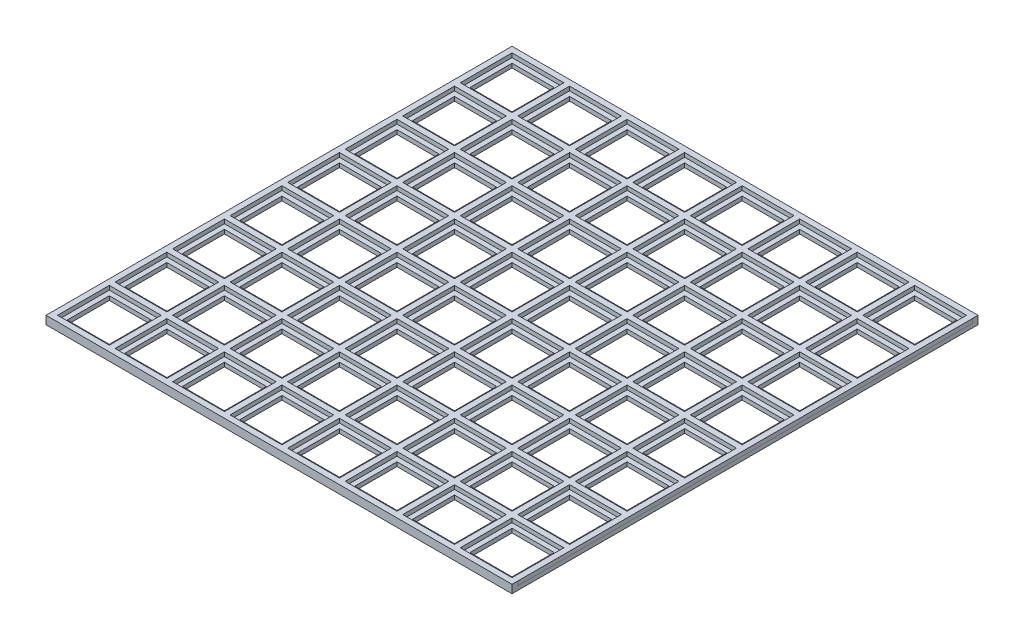
SolidWorks part; units mm, degrees
ref_plane "Front Plane" through (0, 0, 0) normal (0, 0, 1) x (1, 0, 0)
ref_plane "Top Plane" through (0, 0, 0) normal (0, 1, 0) x (1, 0, 0)
ref_plane "Right Plane" through (0, 0, 0) normal (1, 0, 0) x (0, 0, -1)
sketch "Sketch5" plane through (0, 0, 0) normal (1, 0, 0) x (0, 0, -1)
  line L4 (-23.4192, -2.2554) -> (-23.4192, 2.8246)
  line L5 (-23.4192, 2.8246) -> (-19.8632, 2.8246)
  line L6 (-19.8632, 2.8246) -> (-19.8632, 0.2846)
  line L7 (-19.8632, 0.2846) -> (261.0568, 0.2846)
  line L11 (261.0568, 0.2846) -> (261.0568, 2.8246)
  line L12 (261.0568, 2.8246) -> (264.6128, 2.8246)
  line L13 (264.6128, 2.8246) -> (264.6128, -2.2554)
  line L20 (-19.8632, -2.2554) -> (261.0528, -2.2554)
  line L26 (-19.8632, -2.2554) -> (-23.4192, -2.2554)
  line L27 (261.0528, -2.2554) -> (264.6128, -2.2554)
  dimension "D3" = 3.556
  dimension "D4" = 3.556
  dimension "D9" = 2.54
  dimension "D12" = 2.54
  dimension "D14" = 280.92
  dimension "D16" = 2.54
extrude "Boss-Extrude3" add sketch "Sketch5" along normal blind 288.04
sketch "Sketch7" plane through (0, 0.2846, 0) normal (0, 1, 0) x (1, 0, 0)
  line L0 (288.04, 261.0568) -> (0, 261.0568) construction
  line L1 (0.0237, 261.0568) -> (3.5797, 261.0568)
  line L2 (0.0237, 261.0568) -> (0.0237, -19.8632)
  line L3 (0.0237, -19.8632) -> (3.5797, -19.8632)
  line L4 (3.5797, 261.0568) -> (3.5797, -19.8632)
  line L5 (288.04, -19.8632) -> (0, -19.8632) construction
  line L6 (35.5837, 261.0568) -> (35.5837, -19.8632)
  line L7 (35.5837, 261.0568) -> (39.1397, 261.0568)
  line L8 (39.1397, 261.0568) -> (39.1397, -19.8632)
  line L9 (35.5837, -19.8632) -> (39.1397, -19.8632)
  line L10 (71.1437, 261.0568) -> (71.1437, -19.8632)
  line L11 (71.1437, 261.0568) -> (74.6997, 261.0568)
  line L12 (74.6997, 261.0568) -> (74.6997, -19.8632)
  line L13 (71.1437, -19.8632) -> (74.6997, -19.8632)
  line L14 (106.7037, 261.0568) -> (106.7037, -19.8632)
  line L15 (106.7037, 261.0568) -> (110.2597, 261.0568)
  line L16 (110.2597, 261.0568) -> (110.2597, -19.8632)
  line L17 (106.7037, -19.8632) -> (110.2597, -19.8632)
  line L18 (142.2637, 261.0568) -> (142.2637, -19.8632)
  line L19 (142.2637, 261.0568) -> (145.8197, 261.0568)
  line L20 (145.8197, 261.0568) -> (145.8197, -19.8632)
  line L21 (142.2637, -19.8632) -> (145.8197, -19.8632)
  line L22 (177.8237, 261.0568) -> (177.8237, -19.8632)
  line L23 (177.8237, 261.0568) -> (181.3797, 261.0568)
  line L24 (181.3797, 261.0568) -> (181.3797, -19.8632)
  line L25 (177.8237, -19.8632) -> (181.3797, -19.8632)
  line L26 (213.3837, 261.0568) -> (213.3837, -19.8632)
  line L27 (213.3837, 261.0568) -> (216.9397, 261.0568)
  line L28 (216.9397, 261.0568) -> (216.9397, -19.8632)
  line L29 (213.3837, -19.8632) -> (216.9397, -19.8632)
  line L30 (248.9437, 261.0568) -> (248.9437, -19.8632)
  line L31 (248.9437, 261.0568) -> (252.4997, 261.0568)
  line L32 (252.4997, 261.0568) -> (252.4997, -19.8632)
  line L33 (248.9437, -19.8632) -> (252.4997, -19.8632)
  line L34 (284.5037, 261.0568) -> (284.5037, -19.8632)
  line L35 (284.5037, 261.0568) -> (288.0597, 261.0568)
  line L36 (288.0597, 261.0568) -> (288.0597, -19.8632)
  line L37 (284.5037, -19.8632) -> (288.0597, -19.8632)
  line L38 (0.0337, -19.8632) -> (0.0337, -23.4192)
  line L39 (0.0237, -19.8632) -> (288.04, -19.8632)
  line L40 (0.0237, -19.8632) -> (0.0237, -23.4192)
  line L41 (0.0237, -23.4192) -> (288.04, -23.4192)
  line L42 (288.04, -19.8632) -> (288.04, -23.4192)
  line L43 (0.0337, -19.8632) -> (288.05, -19.8632)
  line L44 (288.05, -19.8632) -> (288.05, -23.4192)
  line L45 (0.0337, -23.4192) -> (288.05, -23.4192)
  line L46 (0.0337, 15.6968) -> (0.0337, 12.1408)
  line L47 (0.0337, 15.6968) -> (288.05, 15.6968)
  line L48 (288.05, 15.6968) -> (288.05, 12.1408)
  line L49 (0.0337, 12.1408) -> (288.05, 12.1408)
  line L50 (0.0337, 51.2568) -> (0.0337, 47.7008)
  line L51 (0.0337, 51.2568) -> (288.05, 51.2568)
  line L52 (288.05, 51.2568) -> (288.05, 47.7008)
  line L53 (0.0337, 47.7008) -> (288.05, 47.7008)
  line L54 (0.0337, 86.8168) -> (0.0337, 83.2608)
  line L55 (0.0337, 86.8168) -> (288.05, 86.8168)
  line L56 (288.05, 86.8168) -> (288.05, 83.2608)
  line L57 (0.0337, 83.2608) -> (288.05, 83.2608)
  line L58 (0.0337, 122.3768) -> (0.0337, 118.8208)
  line L59 (0.0337, 122.3768) -> (288.05, 122.3768)
  line L60 (288.05, 122.3768) -> (288.05, 118.8208)
  line L61 (0.0337, 118.8208) -> (288.05, 118.8208)
  line L62 (0.0337, 157.9368) -> (0.0337, 154.3808)
  line L63 (0.0337, 157.9368) -> (288.05, 157.9368)
  line L64 (288.05, 157.9368) -> (288.05, 154.3808)
  line L65 (0.0337, 154.3808) -> (288.05, 154.3808)
  line L66 (0.0337, 193.4968) -> (0.0337, 189.9408)
  line L67 (0.0337, 193.4968) -> (288.05, 193.4968)
  line L68 (288.05, 193.4968) -> (288.05, 189.9408)
  line L69 (0.0337, 189.9408) -> (288.05, 189.9408)
  line L70 (0.0337, 229.0568) -> (0.0337, 225.5008)
  line L71 (0.0337, 229.0568) -> (288.05, 229.0568)
  line L72 (288.05, 229.0568) -> (288.05, 225.5008)
  line L73 (0.0337, 225.5008) -> (288.05, 225.5008)
  line L74 (0.0337, 264.6168) -> (0.0337, 261.0608)
  line L75 (0.0337, 264.6168) -> (288.05, 264.6168)
  line L76 (288.05, 264.6168) -> (288.05, 261.0608)
  line L77 (0.0337, 261.0608) -> (288.05, 261.0608)
  line L78 (0.0237, 15.6968) -> (0.0237, 12.1408)
  line L79 (0.0237, 15.6968) -> (288.04, 15.6968)
  line L80 (288.04, 15.6968) -> (288.04, 12.1408)
  line L81 (0.0237, 12.1408) -> (288.04, 12.1408)
  line L82 (0.0237, 51.2568) -> (0.0237, 47.7008)
  line L83 (0.0237, 51.2568) -> (288.04, 51.2568)
  line L84 (288.04, 51.2568) -> (288.04, 47.7008)
  line L85 (0.0237, 47.7008) -> (288.04, 47.7008)
  line L86 (0.0237, 86.8168) -> (0.0237, 83.2608)
  line L87 (0.0237, 86.8168) -> (288.04, 86.8168)
  line L88 (288.04, 86.8168) -> (288.04, 83.2608)
  line L89 (0.0237, 83.2608) -> (288.04, 83.2608)
  line L90 (0.0237, 122.3768) -> (0.0237, 118.8208)
  line L91 (0.0237, 122.3768) -> (288.04, 122.3768)
  line L92 (288.04, 122.3768) -> (288.04, 118.8208)
  line L93 (0.0237, 118.8208) -> (288.04, 118.8208)
  line L94 (0.0237, 157.9368) -> (0.0237, 154.3808)
  line L95 (0.0237, 157.9368) -> (288.04, 157.9368)
  line L96 (288.04, 157.9368) -> (288.04, 154.3808)
  line L97 (0.0237, 154.3808) -> (288.04, 154.3808)
  line L98 (0.0237, 193.4968) -> (0.0237, 189.9408)
  line L99 (0.0237, 193.4968) -> (288.04, 193.4968)
  line L100 (288.04, 193.4968) -> (288.04, 189.9408)
  line L101 (0.0237, 189.9408) -> (288.04, 189.9408)
  line L102 (0.0237, 229.0568) -> (0.0237, 225.5008)
  line L103 (0.0237, 229.0568) -> (288.04, 229.0568)
  line L104 (288.04, 229.0568) -> (288.04, 225.5008)
  line L105 (0.0237, 225.5008) -> (288.04, 225.5008)
  line L106 (0.0237, 264.6168) -> (0.0237, 261.0608)
  line L107 (0.0237, 264.6168) -> (288.04, 264.6168)
  line L108 (288.04, 264.6168) -> (288.04, 261.0608)
  line L109 (0.0237, 261.0608) -> (288.04, 261.0608)
  dimension "D1" = 3.556
  dimension "D3" = 2
  dimension "D5" = 32.004
  dimension "D6" = 32.004
  dimension "D2" = 9
  dimension "D4" = 9
extrude "Boss-Extrude4" add sketch "Sketch7" along normal blind 2.54 contours L3 L4 L1 L2 | L71 L72 L73 L70 | L6 L9 L8 L7 | L10 L13 L12 L11 | L16 L17 L14 L15 | L18 L21 L20 L19 | L22 L25 L24 L23 | L26 L29 L28 L27 | L30 L33 L32 L31 | L34 L37 L36 L35 | L67 L68 L69 L66 | L63 L64 L65 L62 | L59 L60 L61 L58 | L55 L56 L57 L54 | L51 L52 L53 L50 | L47 L48 L49 L46
sketch "Sketch8" plane through (0, 0.2846, 0) normal (0, 1, 0) x (1, 0, 0)
  line L6 (35.5837, -19.8632) -> (3.5797, -19.8632) construction
  line L7 (6.5797, 9.1368) -> (32.5797, 9.1368)
  line L8 (6.5797, 9.1368) -> (6.5797, -16.8632)
  line L9 (6.5797, -16.8632) -> (32.5797, -16.8632)
  line L10 (32.5797, 9.1368) -> (32.5797, -16.8632)
  line L11 (3.5797, 12.1408) -> (3.5797, -19.8632) construction
  line L12 (42.1397, 9.1368) -> (42.1397, -16.8632)
  line L13 (42.1397, 9.1368) -> (68.1397, 9.1368)
  line L14 (68.1397, 9.1368) -> (68.1397, -16.8632)
  line L15 (42.1397, -16.8632) -> (68.1397, -16.8632)
  line L16 (77.6997, 9.1368) -> (77.6997, -16.8632)
  line L17 (77.6997, 9.1368) -> (103.6997, 9.1368)
  line L18 (103.6997, 9.1368) -> (103.6997, -16.8632)
  line L19 (77.6997, -16.8632) -> (103.6997, -16.8632)
  line L20 (113.2597, 9.1368) -> (113.2597, -16.8632)
  line L21 (113.2597, 9.1368) -> (139.2597, 9.1368)
  line L22 (139.2597, 9.1368) -> (139.2597, -16.8632)
  line L23 (113.2597, -16.8632) -> (139.2597, -16.8632)
  line L24 (148.8197, 9.1368) -> (148.8197, -16.8632)
  line L25 (148.8197, 9.1368) -> (174.8197, 9.1368)
  line L26 (174.8197, 9.1368) -> (174.8197, -16.8632)
  line L27 (148.8197, -16.8632) -> (174.8197, -16.8632)
  line L28 (184.3797, 9.1368) -> (184.3797, -16.8632)
  line L29 (184.3797, 9.1368) -> (210.3797, 9.1368)
  line L30 (210.3797, 9.1368) -> (210.3797, -16.8632)
  line L31 (184.3797, -16.8632) -> (210.3797, -16.8632)
  line L32 (219.9397, 9.1368) -> (219.9397, -16.8632)
  line L33 (219.9397, 9.1368) -> (245.9397, 9.1368)
  line L34 (245.9397, 9.1368) -> (245.9397, -16.8632)
  line L35 (219.9397, -16.8632) -> (245.9397, -16.8632)
  line L36 (255.4997, 9.1368) -> (255.4997, -16.8632)
  line L37 (255.4997, 9.1368) -> (281.4997, 9.1368)
  line L38 (281.4997, 9.1368) -> (281.4997, -16.8632)
  line L39 (255.4997, -16.8632) -> (281.4997, -16.8632)
  line L40 (42.1397, 44.6968) -> (42.1397, 18.6968)
  line L41 (42.1397, 44.6968) -> (68.1397, 44.6968)
  line L42 (68.1397, 44.6968) -> (68.1397, 18.6968)
  line L43 (42.1397, 18.6968) -> (68.1397, 18.6968)
  line L44 (77.6997, 44.6968) -> (77.6997, 18.6968)
  line L45 (77.6997, 44.6968) -> (103.6997, 44.6968)
  line L46 (103.6997, 44.6968) -> (103.6997, 18.6968)
  line L47 (77.6997, 18.6968) -> (103.6997, 18.6968)
  line L48 (113.2597, 44.6968) -> (113.2597, 18.6968)
  line L49 (113.2597, 44.6968) -> (139.2597, 44.6968)
  line L50 (139.2597, 44.6968) -> (139.2597, 18.6968)
  line L51 (113.2597, 18.6968) -> (139.2597, 18.6968)
  line L52 (148.8197, 44.6968) -> (148.8197, 18.6968)
  line L53 (148.8197, 44.6968) -> (174.8197, 44.6968)
  line L54 (174.8197, 44.6968) -> (174.8197, 18.6968)
  line L55 (148.8197, 18.6968) -> (174.8197, 18.6968)
  line L56 (184.3797, 44.6968) -> (184.3797, 18.6968)
  line L57 (184.3797, 44.6968) -> (210.3797, 44.6968)
  line L58 (210.3797, 44.6968) -> (210.3797, 18.6968)
  line L59 (184.3797, 18.6968) -> (210.3797, 18.6968)
  line L60 (219.9397, 44.6968) -> (219.9397, 18.6968)
  line L61 (219.9397, 44.6968) -> (245.9397, 44.6968)
  line L62 (245.9397, 44.6968) -> (245.9397, 18.6968)
  line L63 (219.9397, 18.6968) -> (245.9397, 18.6968)
  line L64 (255.4997, 44.6968) -> (255.4997, 18.6968)
  line L65 (255.4997, 44.6968) -> (281.4997, 44.6968)
  line L66 (281.4997, 44.6968) -> (281.4997, 18.6968)
  line L67 (255.4997, 18.6968) -> (281.4997, 18.6968)
  line L68 (42.1397, 80.2568) -> (42.1397, 54.2568)
  line L69 (42.1397, 80.2568) -> (68.1397, 80.2568)
  line L70 (68.1397, 80.2568) -> (68.1397, 54.2568)
  line L71 (42.1397, 54.2568) -> (68.1397, 54.2568)
  line L72 (77.6997, 80.2568) -> (77.6997, 54.2568)
  line L73 (77.6997, 80.2568) -> (103.6997, 80.2568)
  line L74 (103.6997, 80.2568) -> (103.6997, 54.2568)
  line L75 (77.6997, 54.2568) -> (103.6997, 54.2568)
  line L76 (113.2597, 80.2568) -> (113.2597, 54.2568)
  line L77 (113.2597, 80.2568) -> (139.2597, 80.2568)
  line L78 (139.2597, 80.2568) -> (139.2597, 54.2568)
  line L79 (113.2597, 54.2568) -> (139.2597, 54.2568)
  line L80 (148.8197, 80.2568) -> (148.8197, 54.2568)
  line L81 (148.8197, 80.2568) -> (174.8197, 80.2568)
  line L82 (174.8197, 80.2568) -> (174.8197, 54.2568)
  line L83 (148.8197, 54.2568) -> (174.8197, 54.2568)
  line L84 (184.3797, 80.2568) -> (184.3797, 54.2568)
  line L85 (184.3797, 80.2568) -> (210.3797, 80.2568)
  line L86 (210.3797, 80.2568) -> (210.3797, 54.2568)
  line L87 (184.3797, 54.2568) -> (210.3797, 54.2568)
  line L88 (219.9397, 80.2568) -> (219.9397, 54.2568)
  line L89 (219.9397, 80.2568) -> (245.9397, 80.2568)
  line L90 (245.9397, 80.2568) -> (245.9397, 54.2568)
  line L91 (219.9397, 54.2568) -> (245.9397, 54.2568)
  line L92 (255.4997, 80.2568) -> (255.4997, 54.2568)
  line L93 (255.4997, 80.2568) -> (281.4997, 80.2568)
  line L94 (281.4997, 80.2568) -> (281.4997, 54.2568)
  line L95 (255.4997, 54.2568) -> (281.4997, 54.2568)
  line L96 (42.1397, 115.8168) -> (42.1397, 89.8168)
  line L97 (42.1397, 115.8168) -> (68.1397, 115.8168)
  line L98 (68.1397, 115.8168) -> (68.1397, 89.8168)
  line L99 (42.1397, 89.8168) -> (68.1397, 89.8168)
  line L100 (77.6997, 115.8168) -> (77.6997, 89.8168)
  line L101 (77.6997, 115.8168) -> (103.6997, 115.8168)
  line L102 (103.6997, 115.8168) -> (103.6997, 89.8168)
  line L103 (77.6997, 89.8168) -> (103.6997, 89.8168)
  line L104 (113.2597, 115.8168) -> (113.2597, 89.8168)
  line L105 (113.2597, 115.8168) -> (139.2597, 115.8168)
  line L106 (139.2597, 115.8168) -> (139.2597, 89.8168)
  line L107 (113.2597, 89.8168) -> (139.2597, 89.8168)
  line L108 (148.8197, 115.8168) -> (148.8197, 89.8168)
  line L109 (148.8197, 115.8168) -> (174.8197, 115.8168)
  line L110 (174.8197, 115.8168) -> (174.8197, 89.8168)
  line L111 (148.8197, 89.8168) -> (174.8197, 89.8168)
  line L112 (184.3797, 115.8168) -> (184.3797, 89.8168)
  line L113 (184.3797, 115.8168) -> (210.3797, 115.8168)
  line L114 (210.3797, 115.8168) -> (210.3797, 89.8168)
  line L115 (184.3797, 89.8168) -> (210.3797, 89.8168)
  line L116 (219.9397, 115.8168) -> (219.9397, 89.8168)
  line L117 (219.9397, 115.8168) -> (245.9397, 115.8168)
  line L118 (245.9397, 115.8168) -> (245.9397, 89.8168)
  line L119 (219.9397, 89.8168) -> (245.9397, 89.8168)
  line L120 (255.4997, 115.8168) -> (255.4997, 89.8168)
  line L121 (255.4997, 115.8168) -> (281.4997, 115.8168)
  line L122 (281.4997, 115.8168) -> (281.4997, 89.8168)
  line L123 (255.4997, 89.8168) -> (281.4997, 89.8168)
  line L124 (42.1397, 151.3768) -> (42.1397, 125.3768)
  line L125 (42.1397, 151.3768) -> (68.1397, 151.3768)
  line L126 (68.1397, 151.3768) -> (68.1397, 125.3768)
  line L127 (42.1397, 125.3768) -> (68.1397, 125.3768)
  line L128 (77.6997, 151.3768) -> (77.6997, 125.3768)
  line L129 (77.6997, 151.3768) -> (103.6997, 151.3768)
  line L130 (103.6997, 151.3768) -> (103.6997, 125.3768)
  line L131 (77.6997, 125.3768) -> (103.6997, 125.3768)
  line L132 (113.2597, 151.3768) -> (113.2597, 125.3768)
  line L133 (113.2597, 151.3768) -> (139.2597, 151.3768)
  line L134 (139.2597, 151.3768) -> (139.2597, 125.3768)
  line L135 (113.2597, 125.3768) -> (139.2597, 125.3768)
  line L136 (148.8197, 151.3768) -> (148.8197, 125.3768)
  line L137 (148.8197, 151.3768) -> (174.8197, 151.3768)
  line L138 (174.8197, 151.3768) -> (174.8197, 125.3768)
  line L139 (148.8197, 125.3768) -> (174.8197, 125.3768)
  line L140 (184.3797, 151.3768) -> (184.3797, 125.3768)
  line L141 (184.3797, 151.3768) -> (210.3797, 151.3768)
  line L142 (210.3797, 151.3768) -> (210.3797, 125.3768)
  line L143 (184.3797, 125.3768) -> (210.3797, 125.3768)
  line L144 (219.9397, 151.3768) -> (219.9397, 125.3768)
  line L145 (219.9397, 151.3768) -> (245.9397, 151.3768)
  line L146 (245.9397, 151.3768) -> (245.9397, 125.3768)
  line L147 (219.9397, 125.3768) -> (245.9397, 125.3768)
  line L148 (255.4997, 151.3768) -> (255.4997, 125.3768)
  line L149 (255.4997, 151.3768) -> (281.4997, 151.3768)
  line L150 (281.4997, 151.3768) -> (281.4997, 125.3768)
  line L151 (255.4997, 125.3768) -> (281.4997, 125.3768)
  line L152 (42.1397, 186.9368) -> (42.1397, 160.9368)
  line L153 (42.1397, 186.9368) -> (68.1397, 186.9368)
  line L154 (68.1397, 186.9368) -> (68.1397, 160.9368)
  line L155 (42.1397, 160.9368) -> (68.1397, 160.9368)
  line L156 (77.6997, 186.9368) -> (77.6997, 160.9368)
  line L157 (77.6997, 186.9368) -> (103.6997, 186.9368)
  line L158 (103.6997, 186.9368) -> (103.6997, 160.9368)
  line L159 (77.6997, 160.9368) -> (103.6997, 160.9368)
  line L160 (113.2597, 186.9368) -> (113.2597, 160.9368)
  line L161 (113.2597, 186.9368) -> (139.2597, 186.9368)
  line L162 (139.2597, 186.9368) -> (139.2597, 160.9368)
  line L163 (113.2597, 160.9368) -> (139.2597, 160.9368)
  line L164 (148.8197, 186.9368) -> (148.8197, 160.9368)
  line L165 (148.8197, 186.9368) -> (174.8197, 186.9368)
  line L166 (174.8197, 186.9368) -> (174.8197, 160.9368)
  line L167 (148.8197, 160.9368) -> (174.8197, 160.9368)
  line L168 (184.3797, 186.9368) -> (184.3797, 160.9368)
  line L169 (184.3797, 186.9368) -> (210.3797, 186.9368)
  line L170 (210.3797, 186.9368) -> (210.3797, 160.9368)
  line L171 (184.3797, 160.9368) -> (210.3797, 160.9368)
  line L172 (219.9397, 186.9368) -> (219.9397, 160.9368)
  line L173 (219.9397, 186.9368) -> (245.9397, 186.9368)
  line L174 (245.9397, 186.9368) -> (245.9397, 160.9368)
  line L175 (219.9397, 160.9368) -> (245.9397, 160.9368)
  line L176 (255.4997, 186.9368) -> (255.4997, 160.9368)
  line L177 (255.4997, 186.9368) -> (281.4997, 186.9368)
  line L178 (281.4997, 186.9368) -> (281.4997, 160.9368)
  line L179 (255.4997, 160.9368) -> (281.4997, 160.9368)
  line L180 (42.1397, 222.4968) -> (42.1397, 196.4968)
  line L181 (42.1397, 222.4968) -> (68.1397, 222.4968)
  line L182 (68.1397, 222.4968) -> (68.1397, 196.4968)
  line L183 (42.1397, 196.4968) -> (68.1397, 196.4968)
  line L184 (77.6997, 222.4968) -> (77.6997, 196.4968)
  line L185 (77.6997, 222.4968) -> (103.6997, 222.4968)
  line L186 (103.6997, 222.4968) -> (103.6997, 196.4968)
  line L187 (77.6997, 196.4968) -> (103.6997, 196.4968)
  line L188 (113.2597, 222.4968) -> (113.2597, 196.4968)
  line L189 (113.2597, 222.4968) -> (139.2597, 222.4968)
  line L190 (139.2597, 222.4968) -> (139.2597, 196.4968)
  line L191 (113.2597, 196.4968) -> (139.2597, 196.4968)
  line L192 (148.8197, 222.4968) -> (148.8197, 196.4968)
  line L193 (148.8197, 222.4968) -> (174.8197, 222.4968)
  line L194 (174.8197, 222.4968) -> (174.8197, 196.4968)
  line L195 (148.8197, 196.4968) -> (174.8197, 196.4968)
  line L196 (184.3797, 222.4968) -> (184.3797, 196.4968)
  line L197 (184.3797, 222.4968) -> (210.3797, 222.4968)
  line L198 (210.3797, 222.4968) -> (210.3797, 196.4968)
  line L199 (184.3797, 196.4968) -> (210.3797, 196.4968)
  line L200 (219.9397, 222.4968) -> (219.9397, 196.4968)
  line L201 (219.9397, 222.4968) -> (245.9397, 222.4968)
  line L202 (245.9397, 222.4968) -> (245.9397, 196.4968)
  line L203 (219.9397, 196.4968) -> (245.9397, 196.4968)
  line L204 (255.4997, 222.4968) -> (255.4997, 196.4968)
  line L205 (255.4997, 222.4968) -> (281.4997, 222.4968)
  line L206 (281.4997, 222.4968) -> (281.4997, 196.4968)
  line L207 (255.4997, 196.4968) -> (281.4997, 196.4968)
  line L208 (42.1397, 258.0568) -> (42.1397, 232.0568)
  line L209 (42.1397, 258.0568) -> (68.1397, 258.0568)
  line L210 (68.1397, 258.0568) -> (68.1397, 232.0568)
  line L211 (42.1397, 232.0568) -> (68.1397, 232.0568)
  line L212 (77.6997, 258.0568) -> (77.6997, 232.0568)
  line L213 (77.6997, 258.0568) -> (103.6997, 258.0568)
  line L214 (103.6997, 258.0568) -> (103.6997, 232.0568)
  line L215 (77.6997, 232.0568) -> (103.6997, 232.0568)
  line L216 (113.2597, 258.0568) -> (113.2597, 232.0568)
  line L217 (113.2597, 258.0568) -> (139.2597, 258.0568)
  line L218 (139.2597, 258.0568) -> (139.2597, 232.0568)
  line L219 (113.2597, 232.0568) -> (139.2597, 232.0568)
  line L220 (148.8197, 258.0568) -> (148.8197, 232.0568)
  line L221 (148.8197, 258.0568) -> (174.8197, 258.0568)
  line L222 (174.8197, 258.0568) -> (174.8197, 232.0568)
  line L223 (148.8197, 232.0568) -> (174.8197, 232.0568)
  line L224 (184.3797, 258.0568) -> (184.3797, 232.0568)
  line L225 (184.3797, 258.0568) -> (210.3797, 258.0568)
  line L226 (210.3797, 258.0568) -> (210.3797, 232.0568)
  line L227 (184.3797, 232.0568) -> (210.3797, 232.0568)
  line L228 (219.9397, 258.0568) -> (219.9397, 232.0568)
  line L229 (219.9397, 258.0568) -> (245.9397, 258.0568)
  line L230 (245.9397, 258.0568) -> (245.9397, 232.0568)
  line L231 (219.9397, 232.0568) -> (245.9397, 232.0568)
  line L232 (255.4997, 258.0568) -> (255.4997, 232.0568)
  line L233 (255.4997, 258.0568) -> (281.4997, 258.0568)
  line L234 (281.4997, 258.0568) -> (281.4997, 232.0568)
  line L235 (255.4997, 232.0568) -> (281.4997, 232.0568)
  line L236 (6.5797, 44.6968) -> (6.5797, 18.6968)
  line L237 (6.5797, 44.6968) -> (32.5797, 44.6968)
  line L238 (32.5797, 44.6968) -> (32.5797, 18.6968)
  line L239 (6.5797, 18.6968) -> (32.5797, 18.6968)
  line L240 (6.5797, 80.2568) -> (6.5797, 54.2568)
  line L241 (6.5797, 80.2568) -> (32.5797, 80.2568)
  line L242 (32.5797, 80.2568) -> (32.5797, 54.2568)
  line L243 (6.5797, 54.2568) -> (32.5797, 54.2568)
  line L244 (6.5797, 115.8168) -> (6.5797, 89.8168)
  line L245 (6.5797, 115.8168) -> (32.5797, 115.8168)
  line L246 (32.5797, 115.8168) -> (32.5797, 89.8168)
  line L247 (6.5797, 89.8168) -> (32.5797, 89.8168)
  line L248 (6.5797, 151.3768) -> (6.5797, 125.3768)
  line L249 (6.5797, 151.3768) -> (32.5797, 151.3768)
  line L250 (32.5797, 151.3768) -> (32.5797, 125.3768)
  line L251 (6.5797, 125.3768) -> (32.5797, 125.3768)
  line L252 (6.5797, 186.9368) -> (6.5797, 160.9368)
  line L253 (6.5797, 186.9368) -> (32.5797, 186.9368)
  line L254 (32.5797, 186.9368) -> (32.5797, 160.9368)
  line L255 (6.5797, 160.9368) -> (32.5797, 160.9368)
  line L256 (6.5797, 222.4968) -> (6.5797, 196.4968)
  line L257 (6.5797, 222.4968) -> (32.5797, 222.4968)
  line L258 (32.5797, 222.4968) -> (32.5797, 196.4968)
  line L259 (6.5797, 196.4968) -> (32.5797, 196.4968)
  line L260 (6.5797, 258.0568) -> (6.5797, 232.0568)
  line L261 (6.5797, 258.0568) -> (32.5797, 258.0568)
  line L262 (32.5797, 258.0568) -> (32.5797, 232.0568)
  line L263 (6.5797, 232.0568) -> (32.5797, 232.0568)
  dimension "D1" = 26
  dimension "D2" = 26
  dimension "D3" = 3
  dimension "D4" = 3
  dimension "D5" = 8
  dimension "D6" = 8
extrude "Cut-Extrude1" cut sketch "Sketch8" against normal blind 2.54
